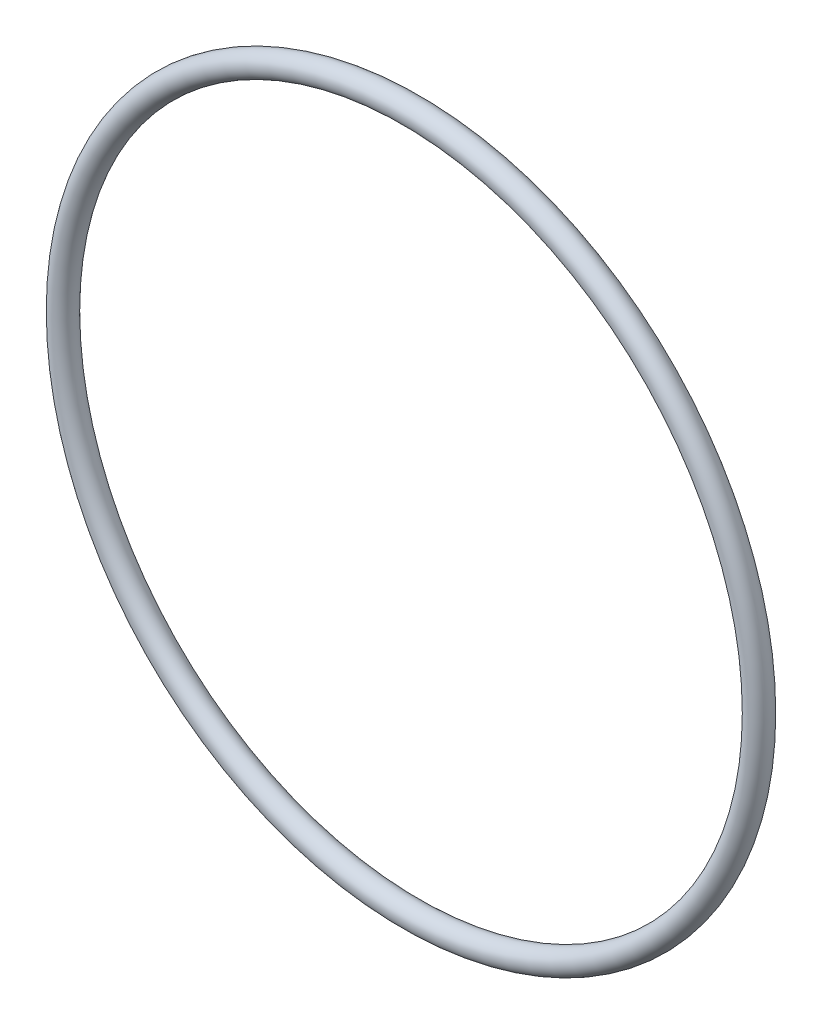
SolidWorks part; units mm, degrees
ref_plane "Front" through (0, 0, 0) normal (0, 0, 1) x (1, 0, 0)
ref_plane "Top" through (0, 0, 0) normal (0, 1, 0) x (1, 0, 0)
ref_plane "Right" through (0, 0, 0) normal (1, 0, 0) x (0, 0, -1)
sketch "Sketch1" plane through (0, 0, 0) normal (1, 0, 0) x (0, -1, 0)
  line L0 (0, -0.889) -> (0, 0.889) construction
  line L2 (-29.7421, 0) -> (29.7421, 0) construction
  line L3 (-25.2603, 0) -> (25.2603, 0) construction
  circle A0 centre (26.1493, 0) radius 0.889
  point P9 (25.2603, 0)
  point P10 (27.0383, 0)
  point P13 (26.1493, 0.889)
  point P14 (26.1493, -0.889)
  dimension "Width" = 1.778
  dimension "ID" = 50.5206
revolve "Revolve1" add sketch "Sketch1" angle 360 about L0
